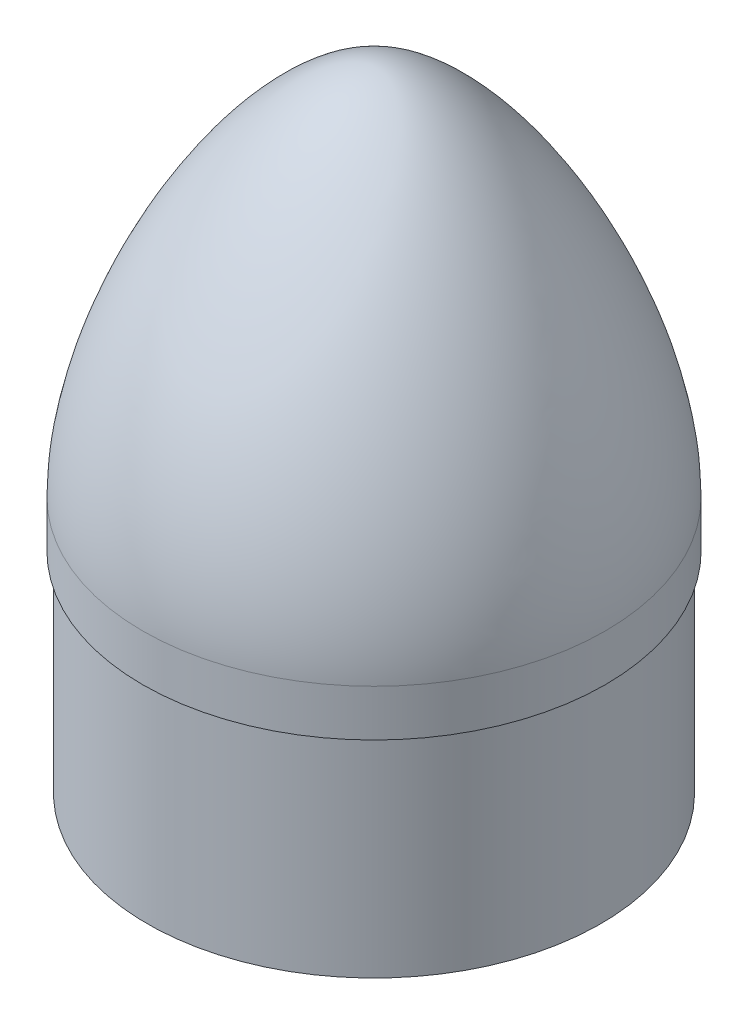
SolidWorks part; units mm, degrees
ref_plane "Front Plane" through (0, 0, 0) normal (0, 0, 1) x (1, 0, 0)
ref_plane "Top Plane" through (0, 0, 0) normal (0, 1, 0) x (1, 0, 0)
ref_plane "Right Plane" through (0, 0, 0) normal (1, 0, 0) x (0, 0, -1)
sketch "Sketch1" plane through (0, 0, 0) normal (0, 0, 1) x (1, 0, 0)
  line L0 (0, 0) -> (0, 78.608) construction
  line L1 (-24.35, 0) -> (-24.35, 22.5)
  line L2 (-24.35, 22.5) -> (-24.85, 22.5)
  line L3 (-24.85, 22.5) -> (-24.85, 27.5)
  line L5 (-23.85, 0) -> (-23.85, 23)
  line L6 (-23.85, 23) -> (-24.35, 23)
  line L7 (-24.35, 23) -> (-24.35, 27.3393)
  line L9 (-24.35, 0) -> (-23.85, 0)
  line L11 (-24.85, 27.5) -> (0.7327, 63.1948) construction
  line L12 (-24.35, 27.3393) -> (1.1391, 62.9036) construction
  line L13 (-24.85, 39.7218) -> (-24.85, 7.8137) construction
  line L14 (16.3696, 67.5) -> (-16.3696, 67.5) construction
  line L15 (-24.3479, 27.8393) -> (-24.3479, 27.8393)
  line L16 (-24.3479, 27.8393) -> (-24.3479, 27.8393)
  line L17 (-24.3479, 27.8393) -> (-24.3479, 27.8393)
  line L18 (-24.3479, 27.8393) -> (-24.3479, 27.8393)
  line L19 (-24.3479, 27.8393) -> (-24.3479, 27.8393)
  line L20 (-24.3479, 27.8393) -> (-24.3479, 27.8393)
  line L21 (-24.3479, 27.8393) -> (-24.3479, 27.8393)
  line L22 (-24.35, 27.3393) -> (-24.3479, 27.8393)
  line L23 (0, 67.5) -> (0, 67)
  spline S0 degree 3 poles (-24.85, 27.5) (-24.85, 43.7802) (-10.2041, 67.5) (0, 67.5) knots 0 0 0 0 1 1 1 1
  spline S1 degree 1 poles (-24.3479, 27.8393) (0, 67) knots 0 0 1 1 construction
  spline S2 degree 3 poles (-24.3479, 27.8393) (-24.3415, 28.346) (-24.3016, 29.3486) (-24.1158, 31.4318) (-23.6931, 34.1082) (-22.9071, 37.4074) (-21.5229, 41.8547) (-19.2302, 47.3921) (-15.7988, 53.636) (-11.911, 59.1151) (-8.4812, 62.7398) (-5.747, 64.893) (-3.7346, 66.0908) (-2.1241, 66.7078) (-0.8859, 66.9578) (-0.2987, 67) (0, 67) knots 0.007054 0.007054 0.007054 0.007054 0.038083 0.069113 0.131172 0.193231 0.25529 0.379408 0.503527 0.627645 0.751763 0.813823 0.875882 0.937941 0.96897 1 1 1 1
  point P27 (0, 78.608)
  dimension "D2" = 23
  dimension "D3" = 0.5
  dimension "D4" = 5
  dimension "D6" = 40
  dimension "D7" = 48.7
  dimension "D1" = 0.5
  dimension "D5" = 0.5
revolve "Revolve1" add sketch "Sketch1" angle 360 about L0
